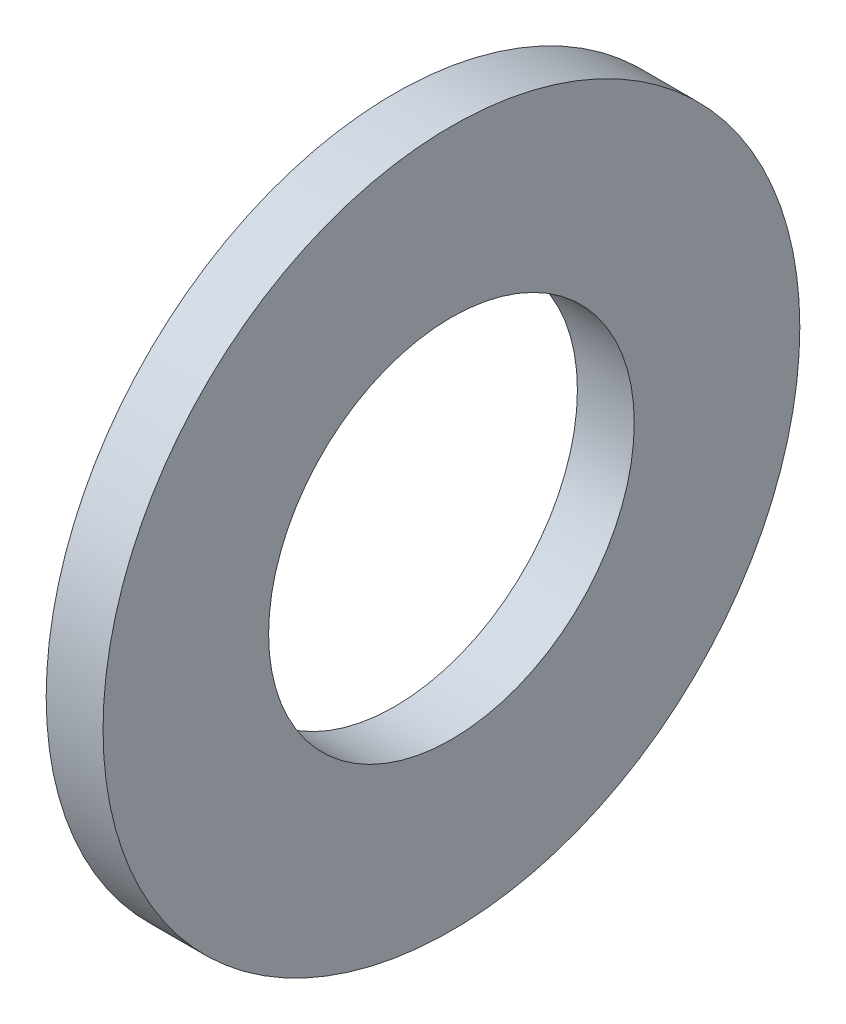
SolidWorks part; units mm, degrees
ref_plane "Front Plane" through (0, 0, 0) normal (0, 0, 1) x (1, 0, 0)
ref_plane "Top Plane" through (0, 0, 0) normal (0, 1, 0) x (1, 0, 0)
ref_plane "Right Plane" through (0, 0, 0) normal (1, 0, 0) x (0, 0, -1)
sketch "Sketch1" plane through (0, 0, 0) normal (1, 0, 0) x (0, 0, -1)
  circle A0 centre (0, 0) radius 7.9375
  circle A1 centre (0, 0) radius 4.1656
  dimension "OD" = 15.875
  dimension "ID" = 8.3312
extrude "Boss-Extrude1" add sketch "Sketch1" along normal blind 1.2954
